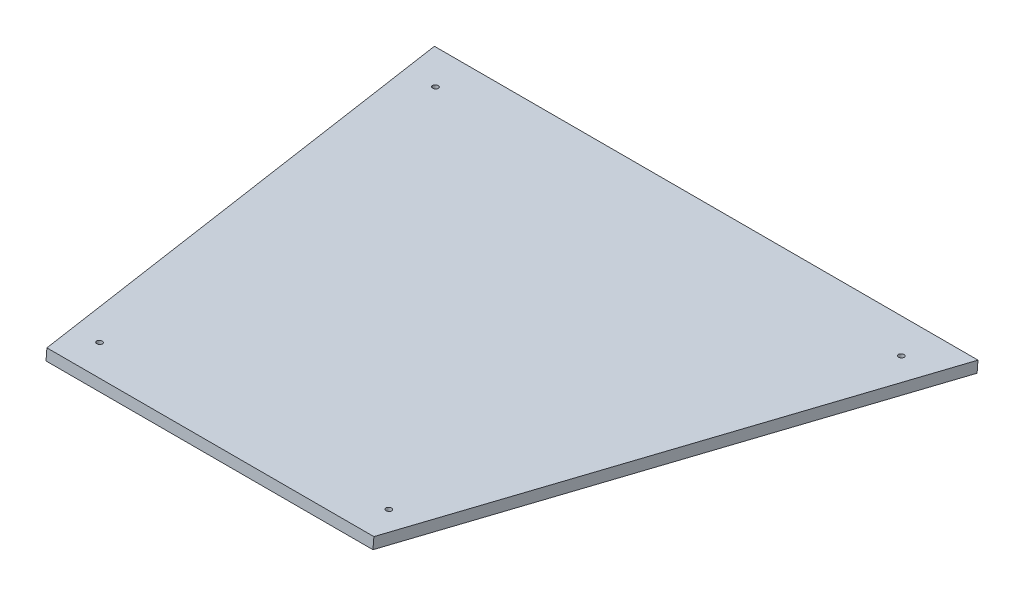
SolidWorks part; units mm, degrees
ref_plane "Front Plane" through (0, 0, 0) normal (0, 0, 1) x (1, 0, 0)
ref_plane "Top Plane" through (0, 0, 0) normal (0, 1, 0) x (1, 0, 0)
ref_plane "Right Plane" through (0, 0, 0) normal (1, 0, 0) x (0, 0, -1)
ref_plane "Plane1" through (-0.0007, -8255.3288, 681.0107) normal (0, -0.9966, 0.0822) x (-1, 0, 0)
sketch "Sketch1" plane through (-0.0007, -8255.3288, 681.0107) normal (0, -0.9966, 0.0822) x (-1, 0, 0)
  line L0 (927.9324, -1893.2884) -> (1306.8393, -1893.2884)
  line L1 (1306.8393, -1893.2884) -> (1432.3521, -1316.7398)
  line L2 (1432.3521, -1316.7398) -> (802.4196, -1316.7398)
  line L3 (802.4196, -1316.7398) -> (927.9324, -1893.2884)
  line L4 (802.4183, -1316.7398) -> (1432.3534, -1316.7398) construction
  line L5 (928.076, -1893.948) -> (801.0629, -1310.5075) construction
  line L6 (1433.7088, -1310.5075) -> (1306.6957, -1893.948) construction
  line L7 (1306.8419, -1893.2884) -> (927.9298, -1893.2884) construction
extrude "Boss-Extrude1" add sketch "Sketch1" along normal blind 12.7
sketch "Sketch2" plane through (-0.0007, -8255.3288, 681.0107) normal (0, 0.9966, -0.0822) x (1, 0, 0)
  line L0 (-927.9324, -1893.2884) -> (-1306.8393, -1893.2884) construction
  line L1 (-1306.8393, -1893.2884) -> (-1432.3521, -1316.7398) construction
  line L2 (-802.4196, -1316.7398) -> (-927.9324, -1893.2884) construction
  line L3 (-1432.3521, -1316.7398) -> (-802.4196, -1316.7398) construction
  circle A0 centre (-1284.9566, -1854.0196) radius 3.175
  circle A3 centre (-949.7975, -1853.9387) radius 3.175
  circle A4 centre (-1387.3011, -1360.7012) radius 3.175
  circle A6 centre (-847.4706, -1360.7012) radius 3.175
  dimension "D1" = 6.35
  dimension "D2" = 39.2688
  dimension "D3" = 29.735
  dimension "D4" = 6.35
  dimension "D5" = 39.3497
  dimension "D7" = 6.35
  dimension "D10" = 6.35
  dimension "D6" = 29.735
  dimension "D8" = 43.9614
  dimension "D9" = 34.6688
  dimension "D11" = 34.6688
  dimension "D12" = 43.9614
extrude "Cut-Extrude1" cut sketch "Sketch2" against normal through all
